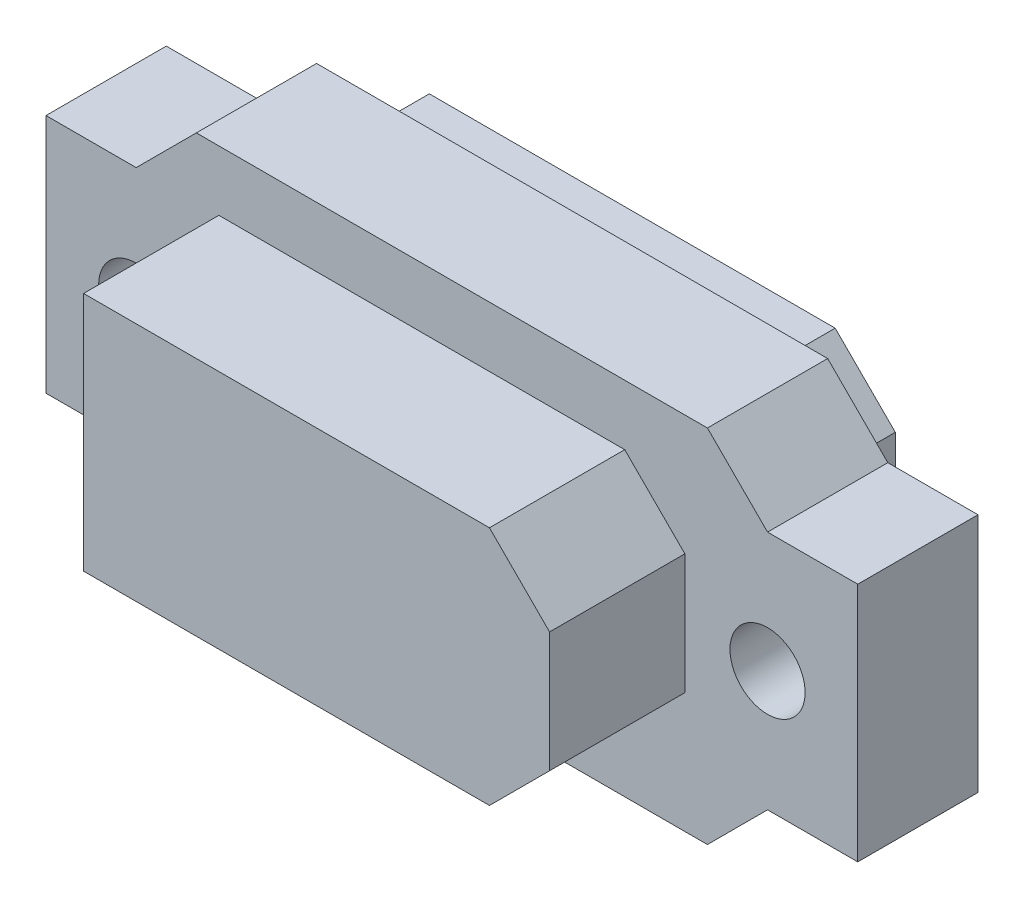
SolidWorks part; units mm, degrees
ref_plane "Přední rovina" through (0, 0, 0) normal (0, 0, 1) x (1, 0, 0)
ref_plane "Horní rovina" through (0, 0, 0) normal (0, 1, 0) x (1, 0, 0)
ref_plane "Pravá rovina" through (0, 0, 0) normal (1, 0, 0) x (0, 0, -1)
sketch "Sketch1" plane through (0, 0, 0) normal (0, 0, 1) x (1, 0, 0)
  line L0 (5.75, -4) -> (7.75, -2)
  line L1 (-7.75, 4) -> (5.75, 4)
  line L2 (-7.75, 4) -> (-7.75, -4)
  line L3 (-7.75, -4) -> (5.75, -4)
  line L4 (7.75, 2) -> (7.75, -2)
  line L5 (-7.75, 4) -> (7.75, -4) construction
  line L6 (-7.75, -4) -> (7.75, 4) construction
  line L11 (-8.88, 2.56) -> (8.88, -2.56) construction
  line L12 (-8.88, -2.56) -> (8.88, 2.56) construction
  line L13 (5.75, 4) -> (7.75, 2)
  line L14 (-7.25, 3.5) -> (-7.25, -3.5)
  line L15 (-7.25, -3.5) -> (5.5429, -3.5)
  line L16 (5.5429, -3.5) -> (7.25, -1.7929)
  line L17 (7.25, 1.7929) -> (7.25, -1.7929)
  line L18 (5.5429, 3.5) -> (7.25, 1.7929)
  line L19 (-7.25, 3.5) -> (5.5429, 3.5)
  point P0 (0, 0)
  point P6 (0, 0)
  dimension "D1" = 8
  dimension "D2" = 15.5
  dimension "D3" = 0.5
extrude "Boss-Extrude1" add sketch "Sketch1" along normal blind 11.5
ref_plane "Plane1" through (0, 0, 3) normal (0, 0, -1) x (-1, 0, 0)
sketch "Sketch2" plane through (0, 0, 3) normal (0, 0, -1) x (-1, 0, 0)
  line L0 (0, 2.6127) -> (0, -2.6127) construction
  line L1 (10.5, 0) -> (-10.5, 0) construction
  line L2 (-13.5, 0) -> (-13.5, 4)
  line L3 (-13.5, 4) -> (-10.5, 4)
  line L4 (-10.5, 4) -> (-8.5, 6)
  line L5 (-8.5, 6) -> (8.5, 6)
  line L6 (7.75, -4) -> (7.75, 4)
  line L7 (7.75, 4) -> (-5.75, 4)
  line L8 (-5.75, 4) -> (-7.75, 2)
  line L9 (-7.75, 2) -> (-7.75, -2)
  line L10 (-7.75, -2) -> (-5.75, -4)
  line L11 (-5.75, -4) -> (7.75, -4)
  line L12 (7.75, -4) -> (7.75, 4)
  line L13 (7.75, 4) -> (-5.75, 4)
  line L14 (-5.75, 4) -> (-7.75, 2)
  line L15 (-7.75, 2) -> (-7.75, -2)
  line L16 (-7.75, -2) -> (-5.75, -4)
  line L17 (-5.75, -4) -> (7.75, -4)
  line L18 (7.75, 2) -> (7.75, -2)
  line L19 (5.75, 4) -> (7.75, 2)
  line L20 (10.5, 4) -> (8.5, 6)
  line L21 (13.5, 4) -> (10.5, 4)
  line L22 (13.5, 0) -> (13.5, 4)
  line L23 (13.5, 0) -> (13.5, -4)
  line L24 (13.5, -4) -> (10.5, -4)
  line L25 (10.5, -4) -> (8.5, -6)
  line L26 (5.75, -4) -> (7.75, -2)
  line L27 (-5.75, -4) -> (-7.75, -2)
  line L28 (7.75, -4) -> (-5.75, -4)
  line L29 (-8.5, -6) -> (8.5, -6)
  line L30 (-10.5, -4) -> (-8.5, -6)
  line L31 (-13.5, -4) -> (-10.5, -4)
  line L32 (-13.5, 0) -> (-13.5, -4)
  circle A0 centre (-10.5, 0) radius 1.25
  circle A1 centre (10.5, 0) radius 1.25
  point P22 (0, 6)
  point P26 (0, 0)
  point P35 (0, -6)
  dimension "D7" = 2.5
  dimension "D8" = 3
  dimension "D2" = 8
  dimension "D3" = 27
  dimension "D4" = 12
  dimension "D5" = 3
  dimension "D6" = 45
  dimension "D1" = 0
extrude "Boss-Extrude2" add sketch "Sketch2" against normal blind 4 contours L2 L32 L31 L30 L29 L25 L24 L23 L22 L21 L20 L5 L4 L3 L17 L16 L15 L14 L13 L12 A0 A1
sketch "Sketch3" plane through (0, 0, 11.5) normal (0, 0, 1) x (1, 0, 0)
  line L0 (-7.25, 3.5) -> (-7.25, -3.5) construction
  line L1 (-7.25, -3.5) -> (5.5429, -3.5) construction
  line L2 (5.5429, -3.5) -> (7.25, -1.7929) construction
  line L3 (7.25, -1.7929) -> (7.25, 1.7929) construction
  line L4 (7.25, 1.7929) -> (5.5429, 3.5) construction
  line L5 (5.5429, 3.5) -> (-7.25, 3.5) construction
  line L6 (-7.25, 3.5) -> (-7.25, -3.5)
  line L7 (-7.25, -3.5) -> (5.5429, -3.5)
  line L8 (5.5429, -3.5) -> (7.25, -1.7929)
  line L9 (7.25, -1.7929) -> (7.25, 1.7929)
  line L10 (7.25, 1.7929) -> (5.5429, 3.5)
  line L11 (5.5429, 3.5) -> (-7.25, 3.5)
extrude "Boss-Extrude3" add sketch "Sketch3" against normal blind 2
sketch "Sketch4" plane through (0, 0, 9.5) normal (0, 0, -1) x (-1, 0, 0)
  circle A0 centre (-4.0125, 0) radius 1.1395
  circle A1 centre (3.8181, 0) radius 1.3834
extrude "Boss-Extrude4" add sketch "Sketch4" along normal blind 9
